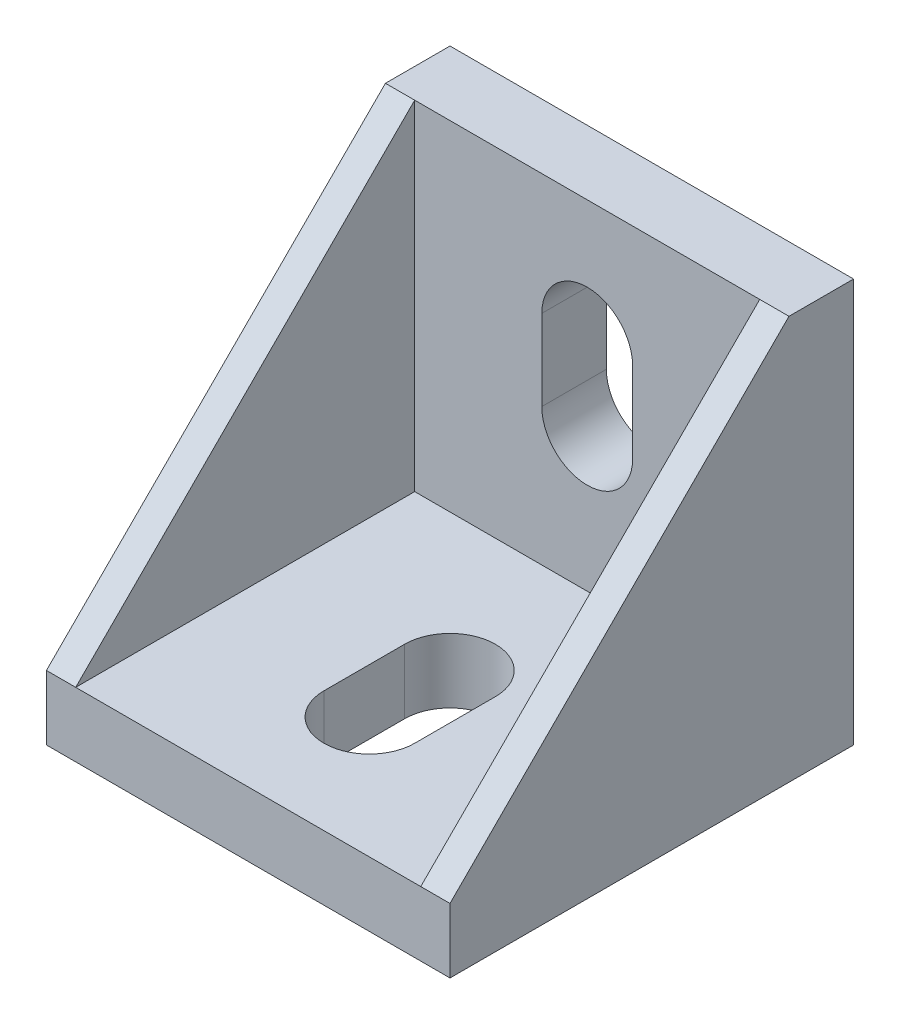
SolidWorks part; units mm, degrees
ref_plane "Front Plane" through (0, 0, 0) normal (0, 0, 1) x (1, 0, 0)
ref_plane "Top Plane" through (0, 0, 0) normal (0, 1, 0) x (1, 0, 0)
ref_plane "Right Plane" through (0, 0, 0) normal (1, 0, 0) x (0, 0, -1)
sketch "Sketch1" plane through (0, 0, 0) normal (0, 0, 1) x (1, 0, 0)
  line L1 (-10, 10) -> (10, 10)
  line L2 (-10, 10) -> (-10, -10)
  line L3 (-10, -10) -> (10, -10)
  line L4 (10, 10) -> (10, -10)
  line L5 (-10, 10) -> (10, -10) construction
  line L6 (-10, -10) -> (10, 10) construction
  point P0 (0, 0)
  dimension "D1" = 20
  dimension "D2" = 20
extrude "Boss-Extrude1" add sketch "Sketch1" along normal blind 20
sketch "Sketch3" plane through (10, 0, 0) normal (1, 0, 0) x (0, 0, -1)
  line L1 (-20, 10) -> (0, 10) construction
  line L2 (-3.2, 10) -> (-20, -6.8)
  line L4 (-20, -10) -> (-20, 10) construction
  line L5 (-20, -6.8) -> (-20, 10)
  line L6 (-20, 10) -> (-3.2, 10)
  line L9 (0, -10) -> (0, 10) construction
  line L10 (-20, -10) -> (0, -10) construction
  dimension "D1" = 3.2
  dimension "D2" = 3.2
extrude "Cut-Extrude2" cut sketch "Sketch3" against normal blind 28 contours L2 L5 L6
ref_plane "Plane2" through (0, 0, 0) normal (-1, 0, 0) x (0, 0, 1)
sketch "Sketch6" plane through (0, 0, 0) normal (-1, 0, 0) x (0, 0, 1)
  line L0 (3.2, 10) -> (3.2, -6.8)
  line L1 (3.2, -6.8) -> (20, -6.8)
  line L2 (20, -6.8) -> (3.2, 10)
  line L3 (20, -10) -> (0, -10) construction
extrude "Cut-Extrude3" cut sketch "Sketch6" against normal mid plane 17.1
sketch "Sketch7" plane through (0, 0, 3.2) normal (0, 0, 1) x (1, 0, 0)
  line L0 (0, 0) -> (0, 4) construction
  line L1 (-2.25, 0) -> (-2.25, 4)
  line L2 (2.25, 0) -> (2.25, 4)
  line L3 (8.55, -6.8) -> (-8.55, -6.8) construction
  line L4 (-8.55, 10) -> (-8.55, -6.8) construction
  arc A0 (-2.25, 0) -> (2.25, 0) centre (0, 0) ccw
  arc A1 (2.25, 4) -> (-2.25, 4) centre (0, 4) ccw
  point P3 (0, 2)
  dimension "D1" = 2.25
  dimension "D2" = 4
extrude "Cut-Extrude4" cut sketch "Sketch7" against normal blind 17.1
sketch "Sketch9" plane through (0, -6.8, 0) normal (0, 1, 0) x (1, 0, 0)
  line L0 (0, -3.2) -> (0, -10) construction
  line L1 (8.55, -3.2) -> (-8.55, -3.2) construction
  line L2 (0, -10) -> (0, -14) construction
  line L3 (2.25, -10) -> (2.25, -14)
  line L4 (-2.25, -10) -> (-2.25, -14)
  arc A0 (2.25, -10) -> (-2.25, -10) centre (0, -10) ccw
  arc A1 (-2.25, -14) -> (2.25, -14) centre (0, -14) ccw
  point P5 (0, -12)
  dimension "D2" = 2.25
  dimension "D1" = 6.8
  dimension "D3" = 4
extrude "Cut-Extrude5" cut sketch "Sketch9" against normal blind 17.1
